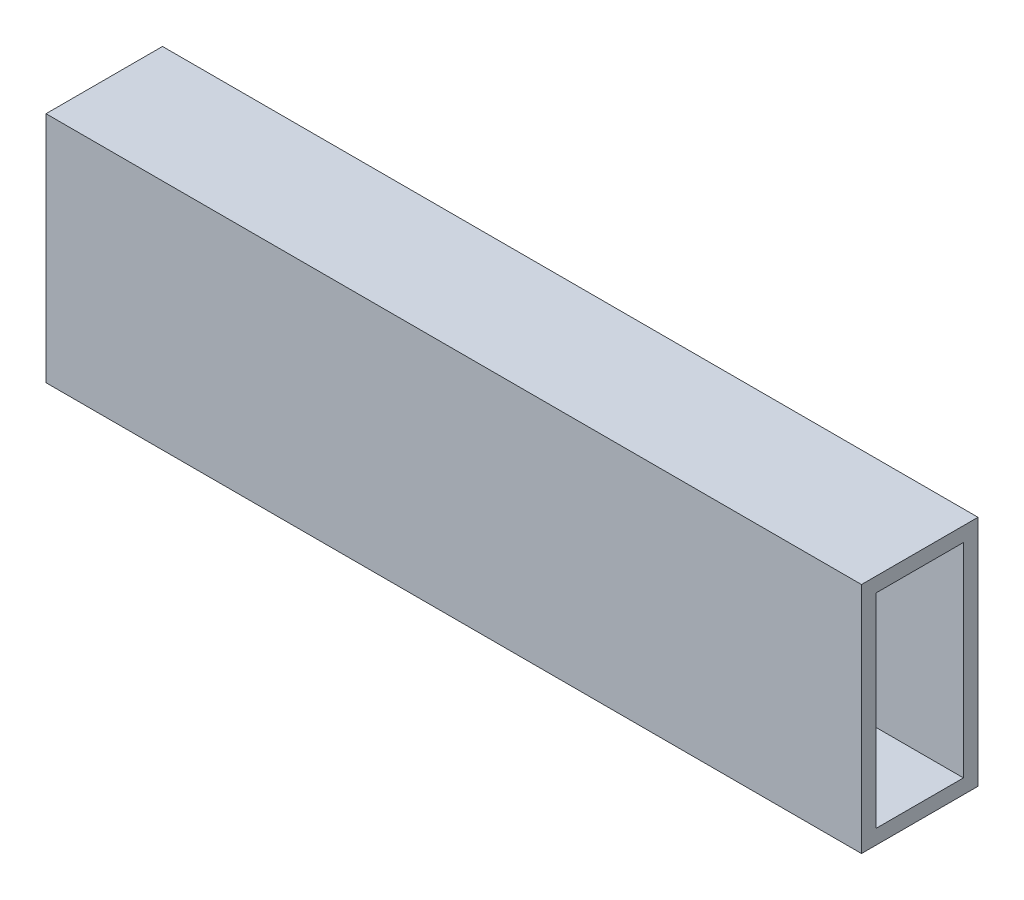
SolidWorks part; units mm, degrees
material "6061 Alloy"
ref_plane "Front Plane" through (0, 0, 0) normal (0, 0, 1) x (1, 0, 0)
ref_plane "Top Plane" through (0, 0, 0) normal (0, 1, 0) x (1, 0, 0)
ref_plane "Right Plane" through (0, 0, 0) normal (1, 0, 0) x (0, 0, -1)
sketch "Sketch1" plane through (0, 0, 0) normal (0, 0, 1) x (1, 0, 0)
  line L1 (0, 0) -> (177.8, 0)
  line L2 (0, 0) -> (0, -50.8)
  line L3 (0, -50.8) -> (177.8, -50.8)
  line L4 (177.8, 0) -> (177.8, -50.8)
extrude "Boss-Extrude1" add sketch "Sketch1" along normal blind 25.4
sketch "Sketch2" plane through (177.8, 0, 0) normal (1, 0, 0) x (0, 0, -1)
  line L0 (-25.4, 0) -> (0, 0) construction
  line L1 (-3.175, -3.175) -> (-22.225, -3.175)
  line L2 (-3.175, -3.175) -> (-3.175, -47.625)
  line L3 (-3.175, -47.625) -> (-22.225, -47.625)
  line L4 (-22.225, -3.175) -> (-22.225, -47.625)
  line L5 (-25.4, -50.8) -> (-25.4, 0) construction
  line L6 (0, -50.8) -> (0, 0) construction
  line L7 (-25.4, -50.8) -> (0, -50.8) construction
  dimension "D1" = 3.175
  dimension "D2" = 3.175
  dimension "D3" = 3.175
  dimension "D4" = 3.175
extrude "Cut-Extrude1" cut sketch "Sketch2" against normal through all
